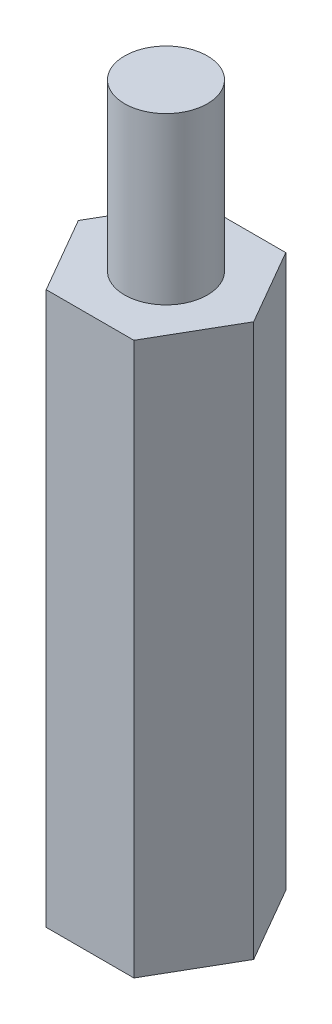
SolidWorks part; units mm, degrees
material "AISI 304"
ref_plane "正面" through (0, 0, 0) normal (0, 0, 1) x (1, 0, 0)
ref_plane "平面" through (0, 0, 0) normal (0, 1, 0) x (1, 0, 0)
ref_plane "右側面" through (0, 0, 0) normal (1, 0, 0) x (0, 0, -1)
sketch "ｽｹｯﾁ1" plane through (0, 0, 0) normal (0, 1, 0) x (1, 0, 0)
  line L1 (1.5877, -2.75) -> (3.1754, 0)
  line L2 (3.1754, 0) -> (1.5877, 2.75)
  line L3 (1.5877, 2.75) -> (-1.5877, 2.75)
  line L4 (-1.5877, 2.75) -> (-3.1754, 0)
  line L5 (-3.1754, 0) -> (-1.5877, -2.75)
  line L6 (-1.5877, -2.75) -> (1.5877, -2.75)
  circle A0 centre (0, 0) radius 2.75 construction
  dimension "D1" = 5.5
extrude "ﾎﾞｽ - 押し出し1" add sketch "ｽｹｯﾁ1" along normal blind 20
sketch "ｽｹｯﾁ2" plane through (0, 20, 0) normal (0, 1, 0) x (1, 0, 0)
  circle A0 centre (0, 0) radius 1.5
  dimension "D1" = 3
extrude "ﾎﾞｽ - 押し出し2" add sketch "ｽｹｯﾁ2" along normal blind 6
cosmetic thread "ねじ山1" parameters "D2"=2
sketch "ｽｹｯﾁ3" plane through (0, 0, 0) normal (0, -1, 0) x (1, 0, 0)
  circle A0 centre (0, 0) radius 1.5
  dimension "D1" = 3
hole_wizard "M3x0.5 ねじ穴1" positions "3Dｽｹｯﾁ2" profile "ｽｹｯﾁ5" tap size "M3x0.5" standard "JIS"
sketch3d "3Dｽｹｯﾁ2"
  point P0 (0, 0, 0)
  point P3 (0, 0, 0)
  point P5 (0, 0, 0)
  point P7 (0, 0, 0)
  point P9 (0, 0, 0)
  dimension "D1" = 0
sketch "ｽｹｯﾁ5" plane through (0, 0, 0) normal (1, 0, 0) x (0, 0, -1)
  line L0 (0, 0) -> (0, 9.2511)
  line L1 (0, 9.2511) -> (1.25, 8.5)
  line L2 (1.25, 8.5) -> (1.25, 0)
  line L5 (1.25, 0) -> (0, 0)
  line L10 (0, 9.2511) -> (-1.25, 8.5) construction
  line L11 (0, -6.35) -> (0, 107.95) construction
  dimension "ねじ下穴ﾄﾞﾘﾙ直径" = 2.5
  dimension "ねじ下穴ﾄﾞﾘﾙの深さ" = 8.5
  dimension "ﾄﾞﾘﾙ角度" = 118
cosmetic thread "穴のねじ山1" parameters "D1"=6, "D2"=3
cosmetic thread "穴のねじ山2" parameters "D1"=6, "D2"=3
cosmetic thread "穴のねじ山3" parameters "D1"=6, "D2"=3
cosmetic thread "穴のねじ山4" parameters "D1"=6, "D2"=3
cosmetic thread "穴のねじ山5" parameters "D1"=6, "D2"=3
